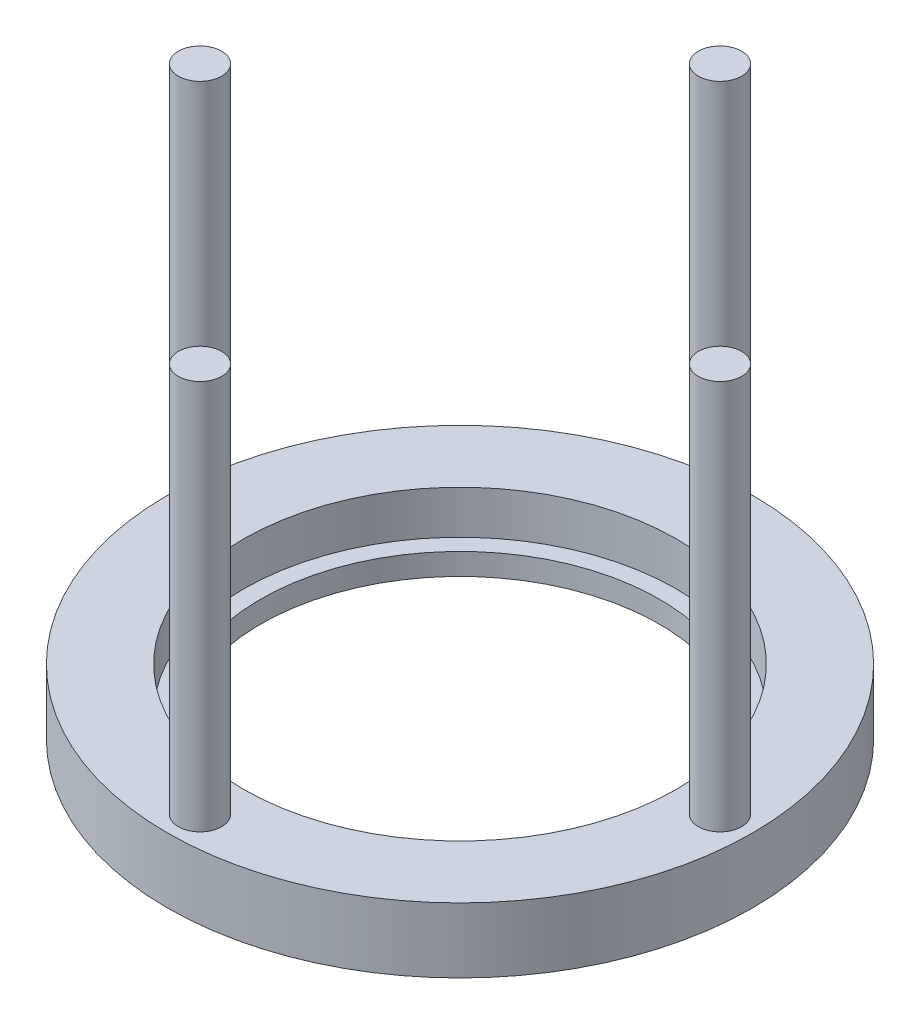
SolidWorks part; units mm, degrees
material "PA Type 6"
ref_plane "Front Plane" through (0, 0, 0) normal (0, 0, 1) x (1, 0, 0)
ref_plane "Top Plane" through (0, 0, 0) normal (0, 1, 0) x (1, 0, 0)
ref_plane "Right Plane" through (0, 0, 0) normal (1, 0, 0) x (0, 0, -1)
sketch "Sketch1" plane through (0, 0, 0) normal (0, 1, 0) x (1, 0, 0)
  circle A0 centre (0, 0) radius 33.75
  dimension "D1" = 67.5
extrude "Boss-Extrude1" add sketch "Sketch1" along normal blind 7.5
sketch "Sketch2" plane through (0, 7.5, 0) normal (0, 1, 0) x (1, 0, 0)
  line L0 (-33.75, 0) -> (33.75, 0) construction
  line L1 (0, 33.75) -> (0, -33.75) construction
  line L2 (0, 0) -> (-23.8649, -23.8649) construction
  circle A0 centre (0, 0) radius 33.75 construction
  circle A1 centre (-30, 0) radius 2.5
  circle A2 centre (30, 0) radius 2.5
  circle A3 centre (0, -30) radius 2.5
  circle A4 centre (0, 30) radius 2.5
  dimension "D2" = 30
  dimension "D3" = 5
  dimension "D1" = 45
extrude "Boss-Extrude2" add sketch "Sketch2" along normal blind 45
sketch "Sketch3" plane through (0, 7.5, 0) normal (0, 1, 0) x (1, 0, 0)
  circle A0 centre (0, 0) radius 25
  dimension "D1" = 50
extrude "Cut-Extrude1" cut sketch "Sketch3" against normal blind 5
sketch "Sketch4" plane through (0, 2.5, 0) normal (0, 1, 0) x (1, 0, 0)
  circle A0 centre (0, 0) radius 23
  dimension "D1" = 46
extrude "Cut-Extrude2" cut sketch "Sketch4" against normal through all
